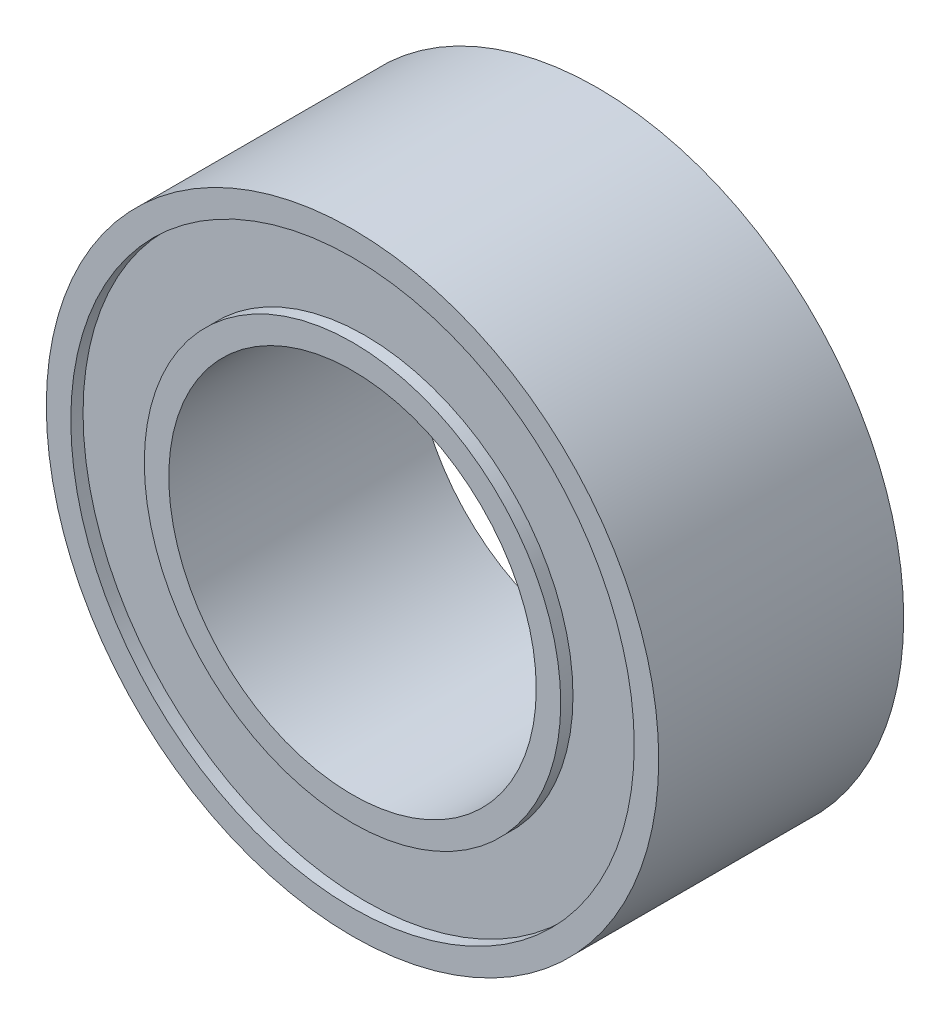
SolidWorks part; units mm, degrees
material "1023 Carbon Steel Sheet (SS)"
ref_plane "Front Plane" through (0, 0, 0) normal (0, 0, 1) x (1, 0, 0)
ref_plane "Top Plane" through (0, 0, 0) normal (0, 1, 0) x (1, 0, 0)
ref_plane "Right Plane" through (0, 0, 0) normal (1, 0, 0) x (0, 0, -1)
sketch "Sketch1" plane through (0, 0, 0) normal (0, 0, 1) x (1, 0, 0)
  circle A0 centre (0, 0) radius 15
  circle A1 centre (0, 0) radius 25
  dimension "D1" = 30
  dimension "D2" = 50
extrude "Boss-Extrude1" add sketch "Sketch1" along normal blind 20
sketch "Sketch2" plane through (0, 0, 20) normal (0, 0, 1) x (1, 0, 0)
  circle A0 centre (0, 0) radius 17
  circle A1 centre (0, 0) radius 23
  dimension "D1" = 34
  dimension "D2" = 46
extrude "Cut-Extrude1" cut sketch "Sketch2" against normal blind 1
sketch "Sketch3" plane through (0, 0, 0) normal (0, 0, -1) x (-1, 0, 0)
  circle A0 centre (0, 0) radius 17
  circle A1 centre (0, 0) radius 23
  dimension "D1" = 34
  dimension "D2" = 46
extrude "Cut-Extrude2" cut sketch "Sketch3" against normal blind 1
